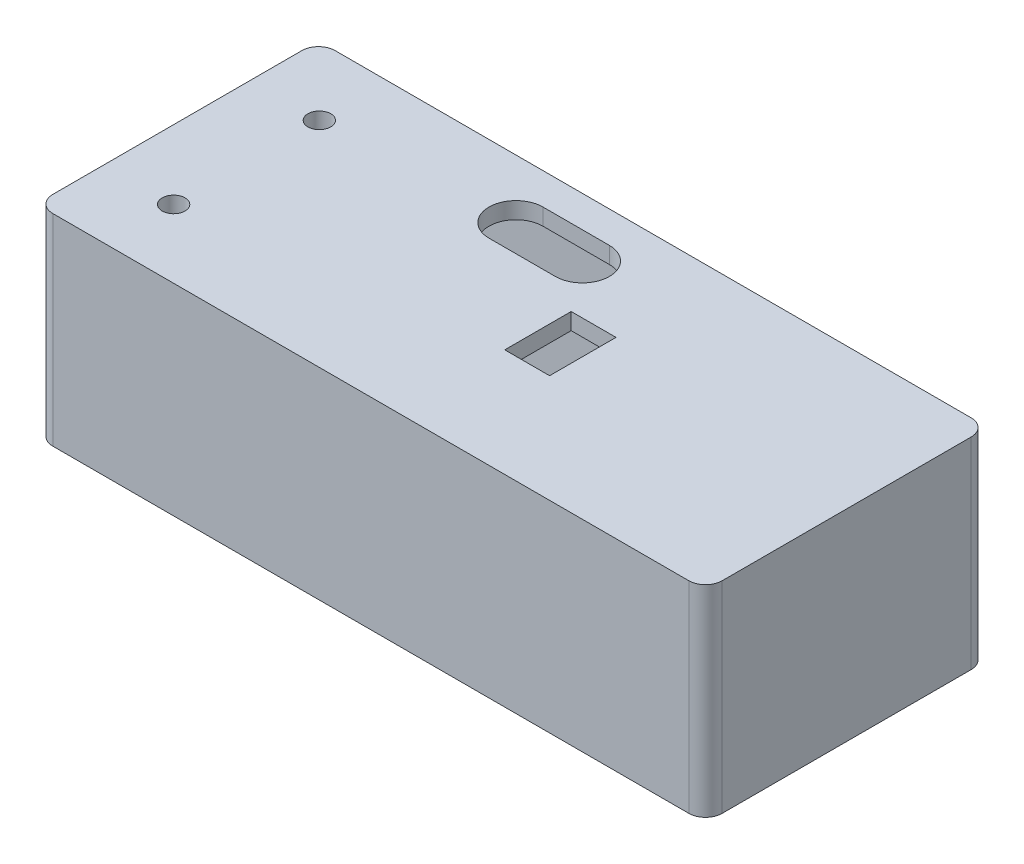
SolidWorks part; units mm, degrees
ref_plane "Front Plane" through (0, 0, 0) normal (0, 0, 1) x (1, 0, 0)
ref_plane "Top Plane" through (0, 0, 0) normal (0, 1, 0) x (1, 0, 0)
ref_plane "Right Plane" through (0, 0, 0) normal (1, 0, 0) x (0, 0, -1)
sketch "Sketch1" plane through (0, 35.4744, 0) normal (0, 1, 0) x (1, 0, 0)
  line L0 (-17.014, -86.8507) -> (80.29, -86.8507) construction
  line L1 (82.83, -84.3107) -> (82.83, -46.2107) construction
  line L2 (80.29, -43.6707) -> (-17.014, -43.6707) construction
  line L3 (-19.554, -46.2107) -> (-19.554, -84.3107) construction
  line L4 (-17.014, -86.8507) -> (80.29, -86.8507)
  line L5 (82.83, -84.3107) -> (82.83, -46.2107)
  line L6 (80.29, -43.6707) -> (-17.014, -43.6707)
  line L7 (-19.554, -46.2107) -> (-19.554, -84.3107)
  line L8 (78.258, -82.4057) -> (78.258, -48.1157) construction
  line L9 (-6.792, -82.4057) -> (78.258, -82.4057) construction
  line L10 (-11.172, -82.4057) -> (-6.792, -82.4057) construction
  line L11 (-14.982, -82.4057) -> (-11.172, -82.4057) construction
  line L12 (-14.982, -79.4057) -> (-14.982, -82.4057) construction
  line L13 (-14.982, -76.4057) -> (-14.982, -79.4057) construction
  line L14 (-14.982, -54.1157) -> (-14.982, -76.4057) construction
  line L15 (-14.982, -51.1157) -> (-14.982, -54.1157) construction
  line L16 (-14.982, -48.1157) -> (-14.982, -51.1157) construction
  line L17 (-11.172, -48.1157) -> (-14.982, -48.1157) construction
  line L18 (-6.792, -48.1157) -> (-11.172, -48.1157) construction
  line L19 (78.258, -48.1157) -> (-6.792, -48.1157) construction
  line L20 (78.258, -82.4057) -> (78.258, -48.1157)
  line L21 (-6.792, -82.4057) -> (78.258, -82.4057)
  line L22 (-11.172, -82.4057) -> (-6.792, -82.4057)
  line L23 (-14.982, -82.4057) -> (-11.172, -82.4057)
  line L24 (-14.982, -79.4057) -> (-14.982, -82.4057)
  line L25 (-14.982, -76.4057) -> (-14.982, -79.4057)
  line L26 (-14.982, -54.1157) -> (-14.982, -76.4057)
  line L27 (-14.982, -51.1157) -> (-14.982, -54.1157)
  line L28 (-14.982, -48.1157) -> (-14.982, -51.1157)
  line L29 (-11.172, -48.1157) -> (-14.982, -48.1157)
  line L30 (-6.792, -48.1157) -> (-11.172, -48.1157)
  line L31 (78.258, -48.1157) -> (-6.792, -48.1157)
  arc A0 (-19.554, -84.3107) -> (-17.014, -86.8507) centre (-17.014, -84.3107) ccw construction
  arc A1 (80.29, -86.8507) -> (82.83, -84.3107) centre (80.29, -84.3107) ccw construction
  arc A2 (82.83, -46.2107) -> (80.29, -43.6707) centre (80.29, -46.2107) ccw construction
  arc A3 (-17.014, -43.6707) -> (-19.554, -46.2107) centre (-17.014, -46.2107) ccw construction
  arc A4 (-19.554, -84.3107) -> (-17.014, -86.8507) centre (-17.014, -84.3107) ccw
  arc A5 (80.29, -86.8507) -> (82.83, -84.3107) centre (80.29, -84.3107) ccw
  arc A6 (82.83, -46.2107) -> (80.29, -43.6707) centre (80.29, -46.2107) ccw
  arc A7 (-17.014, -43.6707) -> (-19.554, -46.2107) centre (-17.014, -46.2107) ccw
extrude "Boss-Extrude1" add sketch "Sketch1" along normal blind 28.2829
sketch "Sketch2" plane through (0, 63.7573, 0) normal (0, 1, 0) x (1, 0, 0)
  line L4 (-17.014, -86.8507) -> (80.29, -86.8507)
  line L5 (82.83, -84.3107) -> (82.83, -46.2107)
  line L6 (80.29, -43.6707) -> (-17.014, -43.6707)
  line L7 (-19.554, -46.2107) -> (-19.554, -84.3107)
  line L8 (-17.014, -86.8507) -> (80.29, -86.8507)
  line L9 (82.83, -84.3107) -> (82.83, -46.2107)
  line L10 (80.29, -43.6707) -> (-17.014, -43.6707)
  line L11 (-19.554, -46.2107) -> (-19.554, -84.3107)
  arc A4 (-19.554, -84.3107) -> (-17.014, -86.8507) centre (-17.014, -84.3107) ccw
  arc A5 (80.29, -86.8507) -> (82.83, -84.3107) centre (80.29, -84.3107) ccw
  arc A6 (82.83, -46.2107) -> (80.29, -43.6707) centre (80.29, -46.2107) ccw
  arc A7 (-17.014, -43.6707) -> (-19.554, -46.2107) centre (-17.014, -46.2107) ccw
  arc A8 (-19.554, -84.3107) -> (-17.014, -86.8507) centre (-17.014, -84.3107) ccw
  arc A9 (80.29, -86.8507) -> (82.83, -84.3107) centre (80.29, -84.3107) ccw
  arc A10 (82.83, -46.2107) -> (80.29, -43.6707) centre (80.29, -46.2107) ccw
  arc A11 (-17.014, -43.6707) -> (-19.554, -46.2107) centre (-17.014, -46.2107) ccw
  dimension "D1" = 0
extrude "Boss-Extrude2" add sketch "Sketch2" along normal blind 2.54
sketch "Sketch3" plane through (0, 66.2973, 0) normal (0, 1, 0) x (1, 0, 0)
  circle A0 centre (-8.982, -54.1157) radius 1.75
  circle A1 centre (-8.982, -76.4057) radius 1.75
  dimension "D1" = 3.5
extrude "Cut-Extrude1" cut sketch "Sketch3" against normal up to next
sketch "Sketch4" plane through (0, 0, 48.1157) normal (0, 0, 1) x (1, 0, 0)
  line L0 (78.258, 34.2044) -> (50.0513, 34.2044) construction
  line L1 (78.258, 34.4584) -> (70.638, 34.4584)
  line L2 (78.258, 34.4584) -> (78.258, 41.4434)
  line L3 (78.258, 41.4434) -> (70.638, 41.4434)
  line L4 (70.638, 34.4584) -> (70.638, 41.4434)
  line L6 (78.258, 63.7573) -> (78.258, 35.4744) construction
  dimension "D1" = 0.254
  dimension "D3" = 7.62
  dimension "D4" = 6.985
extrude "Boss-Extrude3" add sketch "Sketch4" along normal blind 3.81
ref_plane "Plane1" through (0, 0, 65.2607) normal (0, 0, 1) x (1, 0, 0)
mirror "Mirror1" about plane through (0, 0, 65.2607) normal (0, 0, 1) of "Boss-Extrude3"
sketch "Sketch6" plane through (0, 66.2973, 0) normal (0, 1, 0) x (1, 0, 0)
  line L0 (80.29, -43.6707) -> (-17.014, -43.6707) construction
  line L1 (35.61, -60.1807) -> (42.468, -60.1807)
  line L2 (35.61, -60.1807) -> (35.61, -70.3407)
  line L3 (35.61, -70.3407) -> (42.468, -70.3407)
  line L4 (42.468, -60.1807) -> (42.468, -70.3407)
  line L5 (-19.554, -46.2107) -> (-19.554, -84.3107) construction
  dimension "D1" = 16.51
  dimension "D2" = 6.858
  dimension "D3" = 10.16
  dimension "D4" = 55.164
extrude "Cut-Extrude2" cut sketch "Sketch6" against normal up to next
sketch "Sketch7" plane through (0, 66.2973, 0) normal (0, 1, 0) x (1, 0, 0)
  line L0 (29.768, -52.6242) -> (19.608, -52.6242) construction
  line L1 (29.768, -56.7517) -> (19.608, -56.7517)
  line L2 (29.768, -48.4967) -> (19.608, -48.4967)
  line L3 (24.688, -57.6407) -> (24.688, -50.0207) construction
  line L4 (70.638, -48.1157) -> (-14.982, -48.1157) construction
  arc A0 (29.768, -56.7517) -> (29.768, -48.4967) centre (29.768, -52.6242) ccw
  arc A1 (19.608, -48.4967) -> (19.608, -56.7517) centre (19.608, -52.6242) ccw
  point P4 (24.688, -52.6242)
  point P16 (0, 0)
  dimension "D1" = 7.62
  dimension "D2" = 0.381
  dimension "D3" = 8.255
extrude "Cut-Extrude3" cut sketch "Sketch7" against normal up to next
